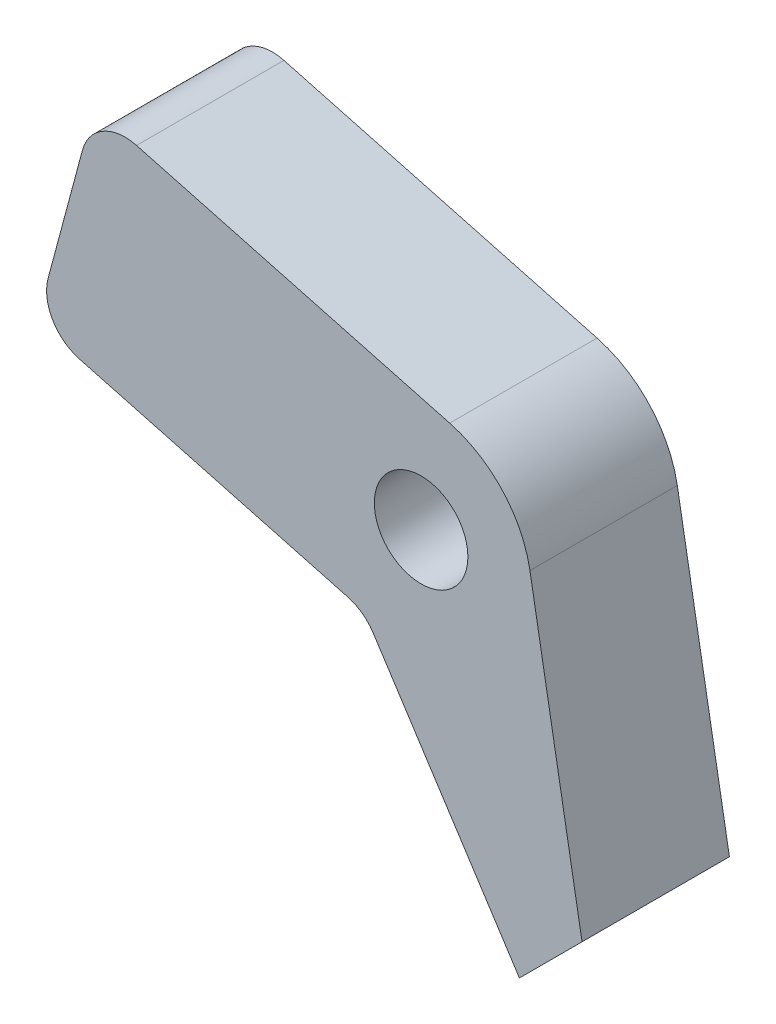
SolidWorks part; units mm, degrees
ref_plane "Front Plane" through (0, 0, 0) normal (0, 0, 1) x (1, 0, 0)
ref_plane "Top Plane" through (0, 0, 0) normal (0, 1, 0) x (1, 0, 0)
ref_plane "Right Plane" through (0, 0, 0) normal (1, 0, 0) x (0, 0, -1)
sketch "Sketch1" plane through (0, 0, 0) normal (0, 0, 1) x (1, 0, 0)
  line L0 (-1.9411, -7.2444) -> (1.9411, 7.2444)
  line L1 (-1.9411, -7.2444) -> (-26.0893, -0.774)
  line L2 (1.9411, 7.2444) -> (-22.207, 13.7149)
  line L3 (-26.0893, -0.774) -> (-22.207, 13.7149)
  line L4 (-7.3861, -1.3024) -> (7.3861, 1.3024)
  line L5 (-7.3861, -1.3024) -> (6.6712, -23)
  line L6 (7.3861, 1.3024) -> (11.6712, -23)
  line L8 (0, 0) -> (50000, 0) construction
  line L9 (0, 0.2555) -> (0, 50000.2555) construction
  line L10 (6.6712, -23) -> (11.6712, -23)
  line L11 (10.9217, -18.7495) -> (6.6712, -23)
  line L13 (0, -23) -> (6.6712, -23)
  circle A0 centre (0, 0) radius 3.175
  circle A1 centre (0, 0) radius 7.5
  point P4 (5.2709, -18.7957)
  point P16 (6.2992, -20)
  dimension "D1" = 6.35
  dimension "D2" = 15
  dimension "D3" = 15
  dimension "D4" = 10
  dimension "D5" = 23
  dimension "D6" = 25
  dimension "D7" = 5
  dimension "D8" = 45
extrude "Boss-Extrude1" add sketch "Sketch1" along normal blind 10
fillet "Fillet1" radius 3 3 edges at (-3.8714, -6.7272, 5) (-22.207, 13.7149, 5) (-26.0893, -0.774, 5)
